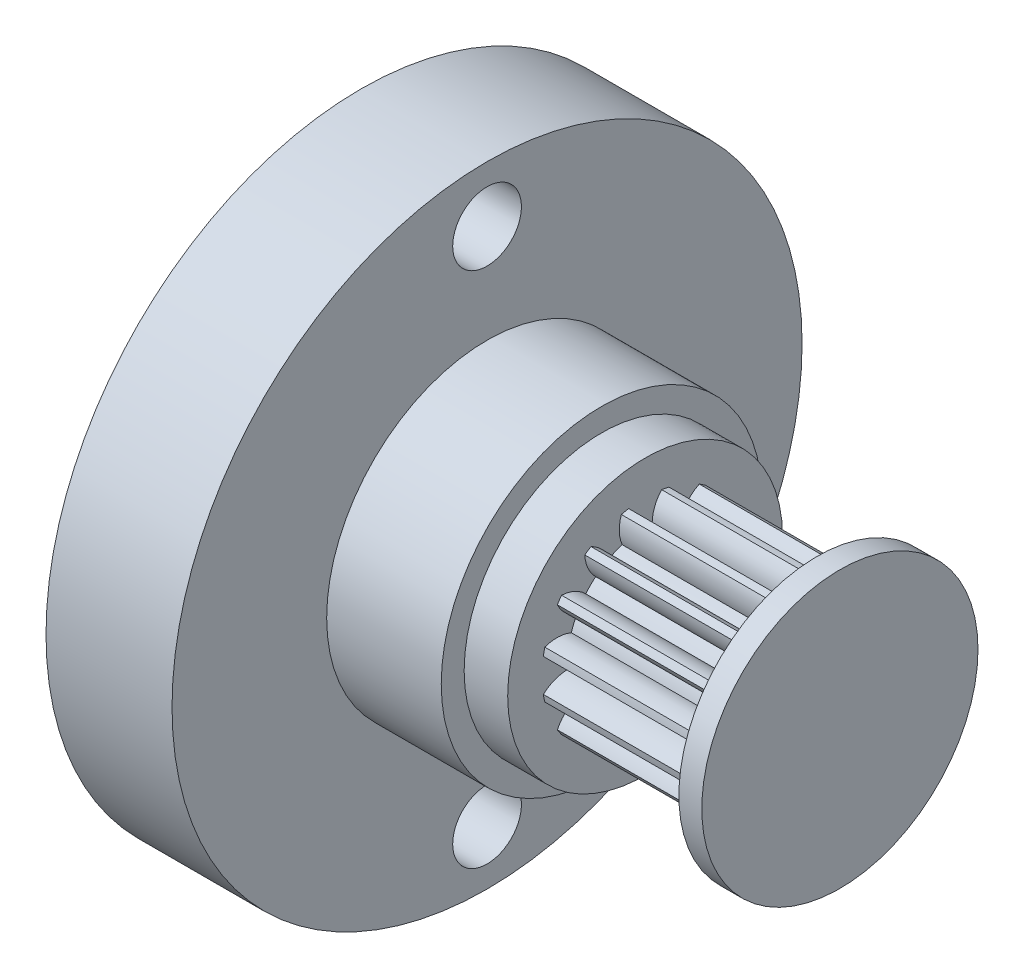
SolidWorks part; units mm, degrees
ref_plane "Plane1" through (0, 0, 0) normal (0, 0, 1) x (1, 0, 0)
ref_plane "Plane2" through (0, 0, 0) normal (0, 1, 0) x (1, 0, 0)
ref_plane "Plane3" through (0, 0, 0) normal (1, 0, 0) x (0, 0, -1)
sketch "HoldingSke" plane through (0, 0, 0) normal (0, 1, 0) x (1, 0, 0)
  line L0 (0, 0) -> (1.9225, -0.5513)
  line L1 (-15, 0) -> (100, 0) construction
  line L2 (0, 0) -> (-2.1039, 2.3779)
  line L3 (0, 0) -> (-11.863, 4.5341)
  line L4 (0, 0) -> (8.3015, 2.3804)
  line L5 (0, 0) -> (-46.8476, -17.4728)
  line L6 (0, 0) -> (-6.2172, -4.1948)
  line L7 (-2.1039, 2.3779) -> (8.6586, 51.2059)
  line L8 (-76.2, 54.61) -> (-75.3, 54.61)
  line L9 (-67.7845, 28.3722) -> (-49.3413, 33.142)
  line L10 (-76.2, 71.12) -> (104.1128, 71.12)
  line L11 (0, 0) -> (-7.5, 0)
  line L12 (-76.2, 101.6) -> (-76.181, 101.6)
  line L13 (24.9733, 27.94) -> (52.9518, 28.4284)
  line L14 (24.9733, 27.94) -> (24.9743, 27.94)
  line L15 (24.9733, 27.94) -> (100.4006, 29.5858)
  line L16 (-63.627, -0.5) -> (-12.827, -0.5)
  circle A0 centre (0, 0) radius 2.5
  circle A1 centre (0, 0) radius 3.374
  circle A2 centre (0, 0) radius 37.5
  circle A3 centre (0, 0) radius 2.5
  dimension "MHD" = 6.748
  dimension "Hub_dia" = 75
  dimension "Bore" = 5
  dimension "MBD" = 5
  dimension "Num_teeth" = 16
  dimension "Pitch" = 2
  dimension "Overall_len" = 50
  dimension "Show_teeth" = 16
  dimension "Thickness" = 7.5
  dimension "OAL" = 50.0001
  dimension "T_dim" = 0.9
  dimension "Ap" = 14.5
  dimension "H" = 19.05
  dimension "Pitch_radius" = 180.3128
  dimension "Width" = 7.5
  dimension "Backlash" = 0.019
  dimension "Addendum_fac" = 1
  dimension "Dedendum_fac" = 1.25
  dimension "Clearance_fac" = 0.25
  dimension "Dedendum_add" = 0.001
  dimension "Module" = 0.5
sketch "BasProSke" plane through (0, 0, 0) normal (0, 1, 0) x (1, 0, 0)
  line L0 (-10, 0) -> (60, 0) construction
  line L1 (0, 0) -> (0, 4.5)
  line L2 (0, 0) -> (7.5, 0)
  line L3 (7.5, 0) -> (7.5, 4.5)
  line L4 (7.5, 4.5) -> (0, 4.5)
  dimension "Thickness" = 7.5
  dimension "Diameter" = 9
revolve "Base-Revolve" add sketch "BasProSke" angle 360 about L0
sketch "TooCutSke" plane through (0, 0, 0) normal (1, 0, 0) x (0, 0, -1)
  line L1 (0, 0) -> (0, 107) construction
  line L2 (0, 0) -> (-0.4253, 3.9773) construction
  line L3 (0, 0) -> (-1.5544, 7.8146) construction
  line L4 (-0.4253, 3.9773) -> (-0.7772, 3.9073) construction
  arc A0 (0.306, 3.3601) -> (-0.306, 3.3601) centre (0, 0) ccw
  arc A1 (0.7382, 4.4648) -> (-0.7382, 4.4648) centre (0, 0) ccw
  circle A2 centre (0, 0) radius 4 construction
  circle A3 centre (0, 0) radius 3.8726 construction
  arc A4 (-0.306, 3.3601) -> (-0.7382, 4.4648) centre (-1.906, 3.3711) ccw
  arc A5 (0.7382, 4.4648) -> (0.306, 3.3601) centre (1.906, 3.3711) ccw
  dimension "Root_dia" = 6.748
  dimension "Overcut_dia" = 9.0508
  dimension "Pitch_dia" = 8
  dimension "Base_dia" = 7.7452
  dimension "Flank_rad" = 1.6
  dimension "Half_ang" = 11.25
  dimension "Half_CT" = 0.3588
extrude "ToothCut" cut sketch "TooCutSke" along normal through all
fillet "Breaks" [suppressed] radius 0.01
fillet "RootFillets" [suppressed] radius 0.126
pattern_circular "TeethCuts" count 16 every 22.5 about axis through (-10, 0, 0) along (1, 0, 0) of "ToothCut", "RootFillets", "Breaks"
sketch "HubNeaOneSke" plane through (0, 0, 0) normal (-1, 0, 0) x (0, 0, 1)
  circle A0 centre (0, 0) radius 3.374
  dimension "Diameter" = 6.748
extrude "HubNearOne" [suppressed] add sketch "HubNeaOneSke" along normal blind 42.5001
sketch "HubNeaBotSke" plane through (0, 0, 0) normal (-1, 0, 0) x (0, 0, 1)
  circle A0 centre (0, 0) radius 3.374
  dimension "Diameter" = 6.748
extrude "HubNearBoth" [suppressed] add sketch "HubNeaBotSke" along normal blind 21.25
ref_plane "FarPln" through (7.5, 0, 0) normal (1, 0, 0) x (0, 0, -1)
sketch "HubFarSke" plane through (7.5, 0, 0) normal (1, 0, 0) x (0, 0, -1)
  circle A0 centre (0, 0) radius 3.374
  dimension "Diameter" = 6.748
extrude "HubFar" [suppressed] add sketch "HubFarSke" along normal blind 21.25
sketch "BorSke" plane through (0, 0, 0) normal (1, 0, 0) x (0, 0, -1)
  circle A0 centre (0, 0) radius 2.5
  dimension "Diameter" = 5
extrude "Bore" cut sketch "BorSke" along normal mid plane 100.0001
sketch "KeySke" plane through (0, 0, 0) normal (1, 0, 0) x (0, 0, -1)
  line L0 (-1, 0) -> (-1, 3.4)
  line L1 (-1, 3.4) -> (1, 3.4)
  line L2 (1, 3.4) -> (1, 0)
  line L3 (0, 0) -> (0, 34) construction
  line L4 (-1, 0) -> (1, 0)
  dimension "Offset" = 3.4
  dimension "Width" = 2
extrude "Keyway" [suppressed] cut sketch "KeySke" along normal mid plane 100.0001
pattern_circular "Keyway2" [suppressed] count 2 every 90 about axis through (-10, 0, 0) along (1, 0, 0)
sketch "Esquisse4" plane through (0, 0, 0) normal (-1, 0, 0) x (0, 0, 1)
  circle A1 centre (0, 0) radius 6
  dimension "D1" = 12
extrude "Boss.-Extru.3" add sketch "Esquisse4" along normal blind 1.9
sketch "Esquisse5" plane through (7.5, 0, 0) normal (1, 0, 0) x (0, 0, -1)
  circle A0 centre (0, 0) radius 2.85
  circle A1 centre (0, 0) radius 6.0278
extrude "Boss.-Extru.4" add sketch "Esquisse5" along normal blind 1
sketch "Esquisse7" plane through (0, 0, 0) normal (1, 0, 0) x (0, 0, -1)
  circle A0 centre (0, 0) radius 3.0071
extrude "Boss.-Extru.6" add sketch "Esquisse7" along normal up to surface (8.5 mm away) up to face at (8.5, 0, -6.0278)
sketch "Esquisse8" plane through (-1.9, 0, 0) normal (-1, 0, 0) x (0, 0, 1)
  circle A0 centre (0, 0) radius 7
  circle A1 centre (0, 0) radius 5.5
  dimension "D1" = 14
  dimension "D2" = 11
extrude "Boss.-Extru.7" add sketch "Esquisse8" along normal blind 7
sketch "Esquisse9" plane through (-8.9, 0, 0) normal (-1, 0, 0) x (0, 0, 1)
  circle A0 centre (0, 0) radius 13.75
  circle A1 centre (0, 0) radius 5.5
  dimension "D1" = 27.5
  dimension "D2" = 11
extrude "Boss.-Extru.8" add sketch "Esquisse9" along normal blind 3.5 and the other way blind 2
sketch "Esquisse10" plane through (-12.4, 0, 0) normal (-1, 0, 0) x (0, 0, 1)
  line L0 (-13.75, 0) -> (13.75, 0) construction
  line L1 (0, 13.75) -> (0, -13.75) construction
  circle A0 centre (0, 11.3) radius 1.5
  circle A1 centre (0, -11.3) radius 1.5
  circle A2 centre (0, 0) radius 13.75 construction
  dimension "D1" = 0
  dimension "D2" = 3
  dimension "D3" = 11.3
  dimension "D4" = 3
  dimension "D5" = 11.3
  dimension "D6" = 0
extrude "Enlèv. mat.-Extru.3" cut sketch "Esquisse10" against normal through all
sketch "Esquisse11" plane through (-1.9, 0, 0) normal (-1, 0, 0) x (0, 0, 1)
  circle A0 centre (0, 0) radius 3
  dimension "D1" = 6
extrude "Enlèv. mat.-Extru.4" cut sketch "Esquisse11" against normal blind 4
sketch "Esquisse13" plane through (2.1, 0, 0) normal (-1, 0, 0) x (0, 0, 1)
  circle A0 centre (0, 0) radius 5.5
extrude "Boss.-Extru.9" add sketch "Esquisse13" along normal blind 10 from surface at 2.1 starting at face at (0, 0, 6)
sketch "Esquisse14" plane through (-10, 0, 0) normal (-1, 0, 0) x (0, 0, 1)
  circle A0 centre (0, 0) radius 5.5
extrude "Enlèv. mat.-Extru.5" cut sketch "Esquisse14" against normal blind 4
sketch "Esquisse15" plane through (-6, 0, 0) normal (-1, 0, 0) x (0, 0, 1)
  circle A0 centre (0, 0) radius 3.3
  dimension "D1" = 6.6
extrude "Boss.-Extru.10" add sketch "Esquisse15" against normal up to surface (14.5 mm away) up to face at (8.5, 0, -6.0278)
equation "' \"Module@HoldingSke\" = 6.35"
equation "' \"Num_teeth@HoldingSke\" = 12"
equation "' \"Ap@HoldingSke\" =  20"
equation "' \"Ap@HoldingSke\" = 20"
equation "' \"Width@HoldingSke\" = 0.5 * 25.4"
equation "' \"Hub_dia@HoldingSke\"= 1 * 25.4"
equation "' \"Hub_dia@HoldingSke\" = 1 * 25.4"
equation "' \"Overall_len@HoldingSke\" = 1.0 * 25.4"
equation "' \"Bore@HoldingSke\" = 0.75 * 25.4"
equation "' \"T_dim@HoldingSke\" = 0.1 * 25.4"
equation "' \"Width@KeySke\" = 0.25 * 25.4"
equation "' \"Show_teeth@HoldingSke\" = 13"
equation "' \"Backlash@HoldingSke\" = 0.009 * 25.4"
equation "' \"Addendum_fac@HoldingSke\" = 1.0"
equation "' \"Dedendum_fac@HoldingSke\" = 1.25"
equation "' \"Dedendum_add@HoldingSke\" = 0.00005 * 25.4"
equation "' \"Clearance_fac@HoldingSke\" = 0.25"
equation "\"Pitch@HoldingSke\" = 1 / \"Module@HoldingSke\""
equation "\"Overcut_dia@TooCutSke\" = (\"Num_teeth@HoldingSke\" + 2 * \"Addendum_fac@HoldingSke\") / \"Pitch@HoldingSke\" + 0.002 * 25.4"
equation "\"Pitch_dia@TooCutSke\" = \"Num_teeth@HoldingSke\" / \"Pitch@HoldingSke\""
equation "\"Base_dia@TooCutSke\" = \"Num_teeth@HoldingSke\" / \"Pitch@HoldingSke\" * cos((\"Ap@HoldingSke\"  * 3.14159265 / 180))"
equation "\"Root_dia@TooCutSke\" = (\"Num_teeth@HoldingSke\" + 2) / \"Pitch@HoldingSke\" - 2 * (\"Addendum_fac@HoldingSke\" + \"Dedendum_fac@HoldingSke\") / \"Pitch@HoldingSke\" - \"Dedendum_add@HoldingSke\" * 2"
equation "\"Half_ang@TooCutSke\" = 180 / \"Num_teeth@HoldingSke\""
equation "\"Half_CT@TooCutSke\" = \"Num_teeth@HoldingSke\" / \"Pitch@HoldingSke\" * sin((3.14159265 / 2 / \"Num_teeth@HoldingSke\")) / 2 - 7 * \"Backlash@HoldingSke\" / 4"
equation "\"Flank_rad@TooCutSke\" = \"Num_teeth@HoldingSke\" / \"Pitch@HoldingSke\" / 5"
equation "\"Radius@RootFillets\" = \"Clearance_fac@HoldingSke\" / \"Pitch@HoldingSke\" + \"Dedendum_add@HoldingSke\""
equation "\"Break_rad@Breaks\" = 0.02 / \"Pitch@HoldingSke\""
equation "\"Thickness@HoldingSke\" = \"Width@HoldingSke\""
equation "\"OAL@HoldingSke\" = \"Thickness@HoldingSke\""
equation "\"MHD@HoldingSke\" = (\"Num_teeth@HoldingSke\" + 2) / \"Pitch@HoldingSke\" - 2 * (\"Addendum_fac@HoldingSke\" + \"Dedendum_fac@HoldingSke\")  / \"Pitch@HoldingSke\" - \"Dedendum_add@HoldingSke\" * 2"
equation "\"MBD@HoldingSke\" = (\"Num_teeth@HoldingSke\" + 2) / \"Pitch@HoldingSke\" - 2 * (\"Addendum_fac@HoldingSke\" + \"Dedendum_fac@HoldingSke\")  / \"Pitch@HoldingSke\" - \"Dedendum_add@HoldingSke\" * 2 - 0.002 * 25.4"
equation "\"MHD@HoldingSke\" = ((sgn( \"MHD@HoldingSke\" - \"Hub_dia@HoldingSke\" )-1)*( \"MHD@HoldingSke\" - \"Hub_dia@HoldingSke\" ))/-2+ \"Hub_dia@HoldingSke\""
equation "\"MBD@HoldingSke\" = ((sgn( \"MBD@HoldingSke\" - \"Bore@HoldingSke\" )-1)*( \"MBD@HoldingSke\" - \"Bore@HoldingSke\" ))/-2+ \"Bore@HoldingSke\""
equation "\"OAL@HoldingSke\" = ((sgn( \"OAL@HoldingSke\" - \"Overall_len@HoldingSke\" )+1)*( \"OAL@HoldingSke\" - \"Overall_len@HoldingSke\" ))/2 + \"Overall_len@HoldingSke\" + 0.000002 * 25.4"
equation "\"Num_teeth@TeethCuts\" = int( \"Show_teeth@HoldingSke\" ) + 1"
equation "\"Num_teeth@TeethCuts\" = ((sgn( \"Num_teeth@TeethCuts\" - \"Num_teeth@HoldingSke\" )-1)*( \"Num_teeth@TeethCuts\" - \"Num_teeth@HoldingSke\" ))/-2+ \"Num_teeth@HoldingSke\""
equation "\"Num_teeth@TeethCuts\" = ((sgn( \"Num_teeth@TeethCuts\" - 2.0)+1)*( \"Num_teeth@TeethCuts\" - 2.0))/2 +2.0"
equation "\"Angle@TeethCuts\" = 360.0 / \"Num_teeth@HoldingSke\""
equation "\"Diameter@BasProSke\" = (\"Num_teeth@HoldingSke\" + 2 * \"Addendum_fac@HoldingSke\") / \"Pitch@HoldingSke\""
equation "\"Thickness@BasProSke\"  = \"Thickness@HoldingSke\""
equation "' \"Fillet_rad@BasProSke\" =  \"Thickness@HoldingSke\" * 0.05"
equation "' \"Fillet_rad@BasProSke\" = \"Thickness@HoldingSke\" * 0.05"
equation "\"MHD@HoldingSke\" = ((sgn( \"MHD@HoldingSke\" - \"Root_dia@TooCutSke\" )-1)*( \"MHD@HoldingSke\" - \"Root_dia@TooCutSke\" ))/-2+ \"Root_dia@TooCutSke\""
equation "\"Diameter@HubNeaOneSke\" = \"MHD@HoldingSke\""
equation "\"Length@HubNearOne\" = \"OAL@HoldingSke\" - \"Thickness@BasProSke\""
equation "\"Diameter@HubNeaBotSke\" = \"MHD@HoldingSke\""
equation "\"Length@HubNearBoth\" = ( \"OAL@HoldingSke\" - \"Thickness@BasProSke\" ) / 2.0"
equation "\"Thickness@FarPln\" = \"Thickness@BasProSke\""
equation "\"Diameter@HubFarSke\" = \"MHD@HoldingSke\""
equation "\"Length@HubFar\" = ( \"OAL@HoldingSke\" - \"Thickness@BasProSke\" ) / 2.0"
equation "\"Diameter@BorSke\" = \"MBD@HoldingSke\""
equation "\"D1@Bore\" = \"OAL@HoldingSke\" * 2.0"
equation "\"D1@Keyway\" = \"OAL@HoldingSke\" * 2.0"
equation "\"Offset@KeySke\" = \"T_dim@HoldingSke\" + \"MBD@HoldingSke\" / 2.0"
